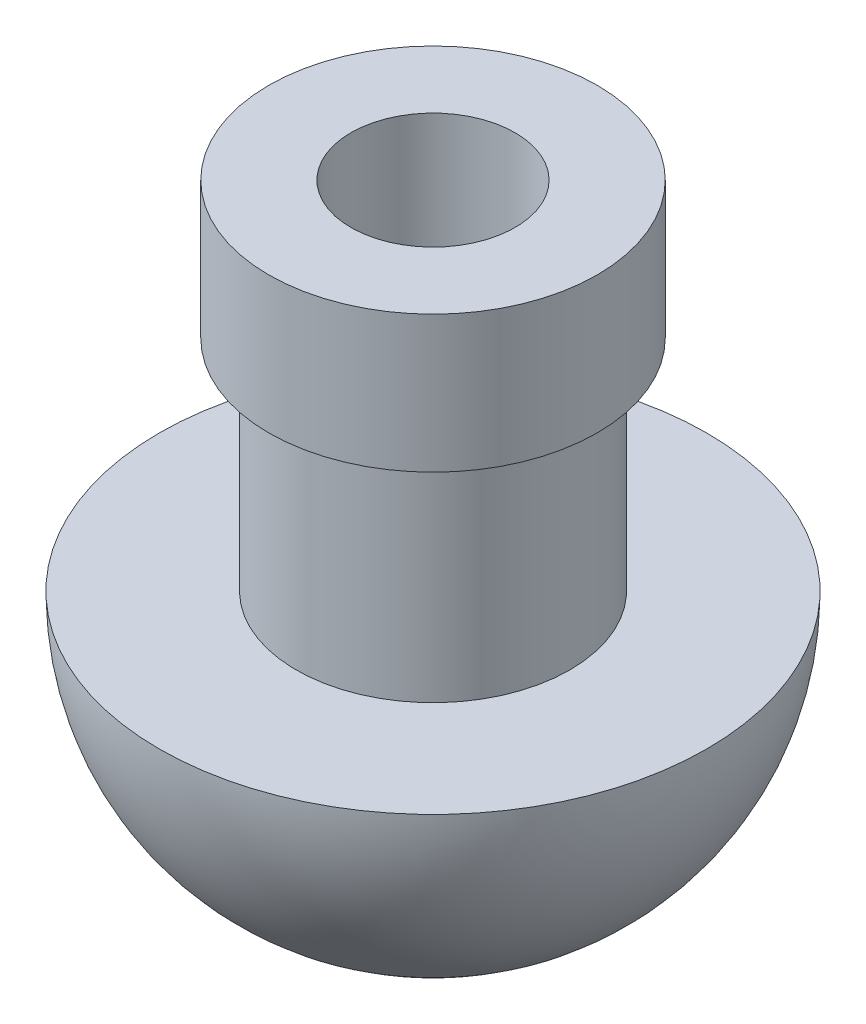
SolidWorks part; units mm, degrees
material "Rubber"
ref_plane "Płaszczyzna przednia" through (0, 0, 0) normal (0, 0, 1) x (1, 0, 0)
ref_plane "Płaszczyzna górna" through (0, 0, 0) normal (0, 1, 0) x (1, 0, 0)
ref_plane "Płaszczyzna prawa" through (0, 0, 0) normal (1, 0, 0) x (0, 0, -1)
sketch "Szkic1" plane through (0, 0, 0) normal (0, 0, 1) x (1, 0, 0)
  line L0 (-10, 0) -> (-5, 0)
  line L3 (-5, 0) -> (-5, 8)
  line L8 (-6, 8) -> (-5, 8)
  line L9 (-6, 8) -> (-6, 13)
  line L10 (-6, 13) -> (0, 13)
  line L12 (0, -10) -> (0, 0)
  line L13 (0, 0) -> (0, 13)
  arc A0 (-10, 0) -> (0, -10) centre (0, 0) ccw
  dimension "D1" = 10
  dimension "D2" = 8
  dimension "D3" = 5
  dimension "D4" = 6
  dimension "D5" = 5
revolve "Obrót5" add sketch "Szkic1" angle 360 about L12
sketch "Szkic2" plane through (0, 13, 0) normal (0, 1, 0) x (1, 0, 0)
  circle A0 centre (0, 0) radius 3
  dimension "D1" = 6
extrude "Wytnij-wyciągnięcie1" cut sketch "Szkic2" against normal up to surface (13 mm away) up to face at (10, 0, 0)
